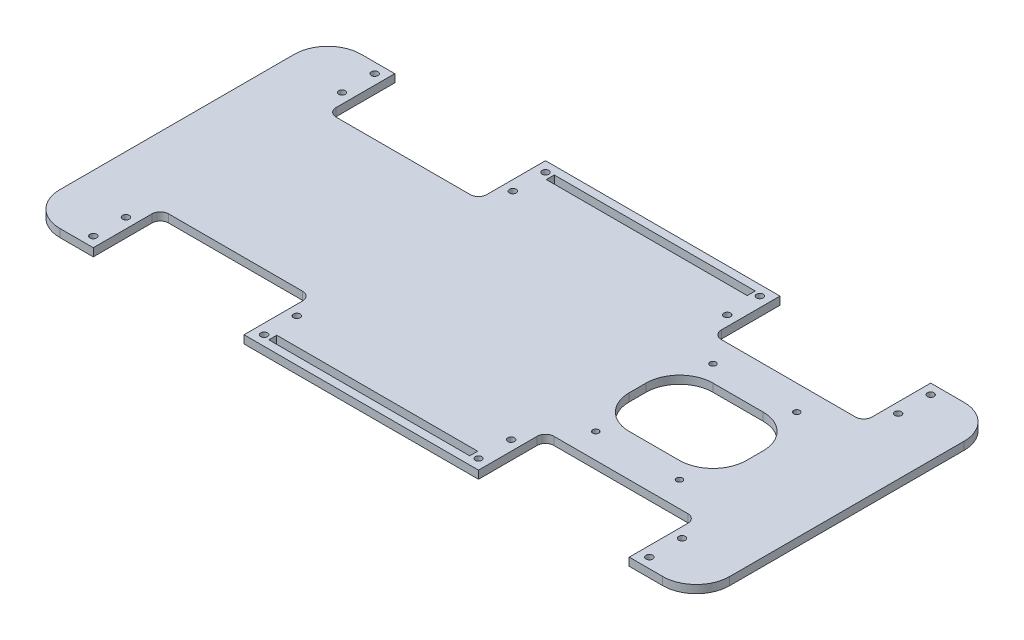
SolidWorks part; units mm, degrees
material "Pine"
ref_plane "Front Plane" through (0, 0, 0) normal (0, 0, 1) x (1, 0, 0)
ref_plane "Top Plane" through (0, 0, 0) normal (0, 1, 0) x (1, 0, 0)
ref_plane "Right Plane" through (0, 0, 0) normal (1, 0, 0) x (0, 0, -1)
sketch "Sketch1" plane through (0, 0, 0) normal (0, 1, 0) x (1, 0, 0)
  line L0 (-160, 50) -> (-160, -50) construction
  line L1 (-200, 90) -> (-160, 90)
  line L2 (-200, 90) -> (-200, -90)
  line L3 (-200, -90) -> (-160, -90)
  line L4 (200, 90) -> (200, -90)
  line L6 (-160, 90) -> (-160, 50)
  line L7 (-160, 50) -> (-70, 50)
  line L8 (-70, 90) -> (-70, 50)
  line L10 (-160, -90) -> (-160, -50)
  line L11 (-160, -50) -> (-70, -50)
  line L12 (-70, -90) -> (-70, -50)
  line L14 (70, -90) -> (70, -50)
  line L15 (70, -50) -> (160, -50)
  line L16 (160, -90) -> (160, -50)
  line L18 (70, 90) -> (70, 50)
  line L19 (70, 50) -> (160, 50)
  line L20 (160, 90) -> (160, 50)
  line L21 (-70, 50) -> (-70, -50) construction
  line L22 (70, -50) -> (-70, -50) construction
  line L23 (-70, 50) -> (70, 50) construction
  line L24 (70, -50) -> (70, 50) construction
  line L25 (-70, 90) -> (70, 90)
  line L26 (-70, -90) -> (70, -90)
  line L27 (160, -90) -> (200, -90)
  line L28 (160, 90) -> (200, 90)
  point P22 (200, 0)
  point P23 (-70, 0)
  point P24 (0, -50)
  dimension "D1" = 90
  dimension "D2" = 40
  dimension "D3" = 400
  dimension "D4" = 40
  dimension "D5" = 180
extrude "Boss-Extrude1" add sketch "Sketch1" along normal mid plane 4.7625
hole_wizard "M3 Clearance Hole1" positions "Sketch3" profile "Sketch4" hole size "M3" standard "ANSI Metric"
sketch "Sketch3" plane through (0, 2.3813, 0) normal (0, 1, 0) x (1, 0, 0)
  line L0 (85, -35) -> (135, -35) construction
  line L1 (135, -35) -> (135, 35) construction
  line L2 (135, 35) -> (85, 35) construction
  line L3 (85, 35) -> (85, -35) construction
  line L4 (85, 35) -> (135, 35)
  point P0 (135, -35)
  point P2 (85, -35)
  point P5 (85, 35)
  point P7 (135, 35)
  dimension "D1" = 50
sketch "Sketch4" plane through (135, 2.3813, 35) normal (1, 0, 0) x (0, 0, 1)
  line L0 (0, 0) -> (0, 11.0815)
  line L1 (0, 11.0815) -> (1.8, 10)
  line L2 (1.8, 10) -> (1.8, 0)
  line L5 (1.8, 0) -> (0, 0)
  line L10 (0, 11.0815) -> (-1.8, 10) construction
  line L11 (0, -6.35) -> (0, 107.95) construction
  dimension "Hole Dia." = 3.6
  dimension "Hole Depth" = 10
  dimension "Drill Angle" = 118
sketch "Sketch5" plane through (0, 2.3813, 0) normal (0, 1, 0) x (1, 0, 0)
  line L1 (-60, 85.2375) -> (60, 85.2375)
  line L2 (-60, 85.2375) -> (-60, 80.475)
  line L3 (-60, 80.475) -> (60, 80.475)
  line L4 (60, 85.2375) -> (60, 80.475)
  line L5 (-60, -80.475) -> (60, -80.475)
  line L6 (-60, -80.475) -> (-60, -85.2375)
  line L7 (-60, -85.2375) -> (60, -85.2375)
  line L8 (60, -80.475) -> (60, -85.2375)
extrude "Cut-Extrude1" cut sketch "Sketch5" against normal blind 10
sketch "Sketch6" plane through (0, -2.3813, 0) normal (0, -1, 0) x (1, 0, 0)
  line L0 (-160, 90) -> (-160, 50) construction
  line L1 (-70, 50) -> (-70, 90) construction
  line L2 (-200, 90) -> (-160, 90) construction
  line L3 (-70, -90) -> (-70, -50) construction
  line L4 (70, -90) -> (-70, -90) construction
  circle A0 centre (-166, 84) radius 2
  circle A1 centre (-166, 64.5) radius 2
  circle A2 centre (-64, 84) radius 2
  circle A3 centre (-64, 64.5) radius 2
  circle A4 centre (-166, -64.5) radius 2
  circle A5 centre (-166, -84) radius 2
  circle A6 centre (-64, -64.5) radius 2
  circle A7 centre (-64, -84) radius 2
  dimension "D1" = 4
  dimension "D5" = 6
  dimension "D10" = 4
  dimension "D2" = 6
  dimension "D3" = 19.5
  dimension "D4" = 6
  dimension "D6" = 6
  dimension "D7" = 6
  dimension "D8" = 19.5
  dimension "D9" = 102
extrude "Cut-Extrude2" cut sketch "Sketch6" against normal blind 10
ref_plane "Plane1" through (0, 0, 0) normal (-1, 0, 0) x (0, 0, 1)
mirror "Mirror1" about plane through (0, 0, 0) normal (-1, 0, 0) of "Cut-Extrude2"
sketch "Sketch7" plane through (0, 2.3813, 0) normal (0, 1, 0) x (1, 0, 0)
  line L0 (200, -90) -> (200, 90) construction
  line L1 (75, 25) -> (145, 25)
  line L2 (75, 25) -> (75, -25)
  line L3 (75, -25) -> (145, -25)
  line L4 (145, 25) -> (145, -25)
  point P4 (75, 0)
  dimension "D1" = 70
  dimension "D2" = 50
  dimension "D3" = 55
extrude "Cut-Extrude3" cut sketch "Sketch7" against normal blind 10
fillet "Fillet1" radius 20 8 edges at (200, 0, -90) (145, 0, 25) (75, 0, 25) (75, 0, -25) (145, 0, -25) (-200, 0, -90) (-200, 0, 90) (200, 0, 90)
fillet "Fillet2" radius 5 8 edges at (70, 0, -50) (160, 0, -50) (-70, 0, -50) (-160, 0, -50) (-70, 0, 50) (-160, 0, 50) (70, 0, 50) (160, 0, 50)
